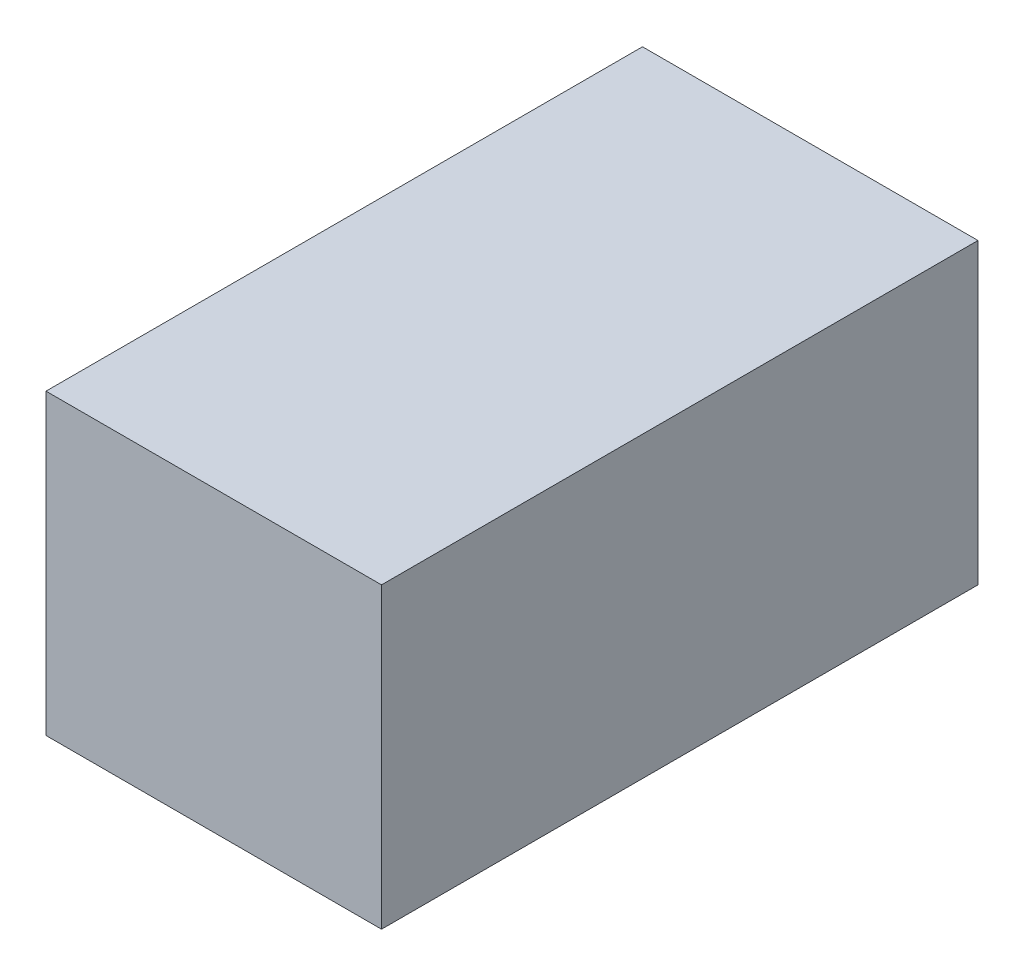
SolidWorks part; units mm, degrees
ref_plane "前视基准面" through (0, 0, 0) normal (0, 0, 1) x (1, 0, 0)
ref_plane "上视基准面" through (0, 0, 0) normal (0, 1, 0) x (1, 0, 0)
ref_plane "右视基准面" through (0, 0, 0) normal (1, 0, 0) x (0, 0, -1)
sketch "草图1" plane through (0, 0, 0) normal (1, 0, 0) x (0, 0, -1)
  line L1 (-20.4399, 42.1151) -> (59.5601, 42.1151)
  line L2 (-20.4399, 42.1151) -> (-20.4399, 2.1151)
  line L3 (-20.4399, 2.1151) -> (59.5601, 2.1151)
  line L4 (59.5601, 42.1151) -> (59.5601, 2.1151)
  dimension "D1" = 80
  dimension "D2" = 40
extrude "凸台-拉伸1" add sketch "草图1" along normal blind 45
